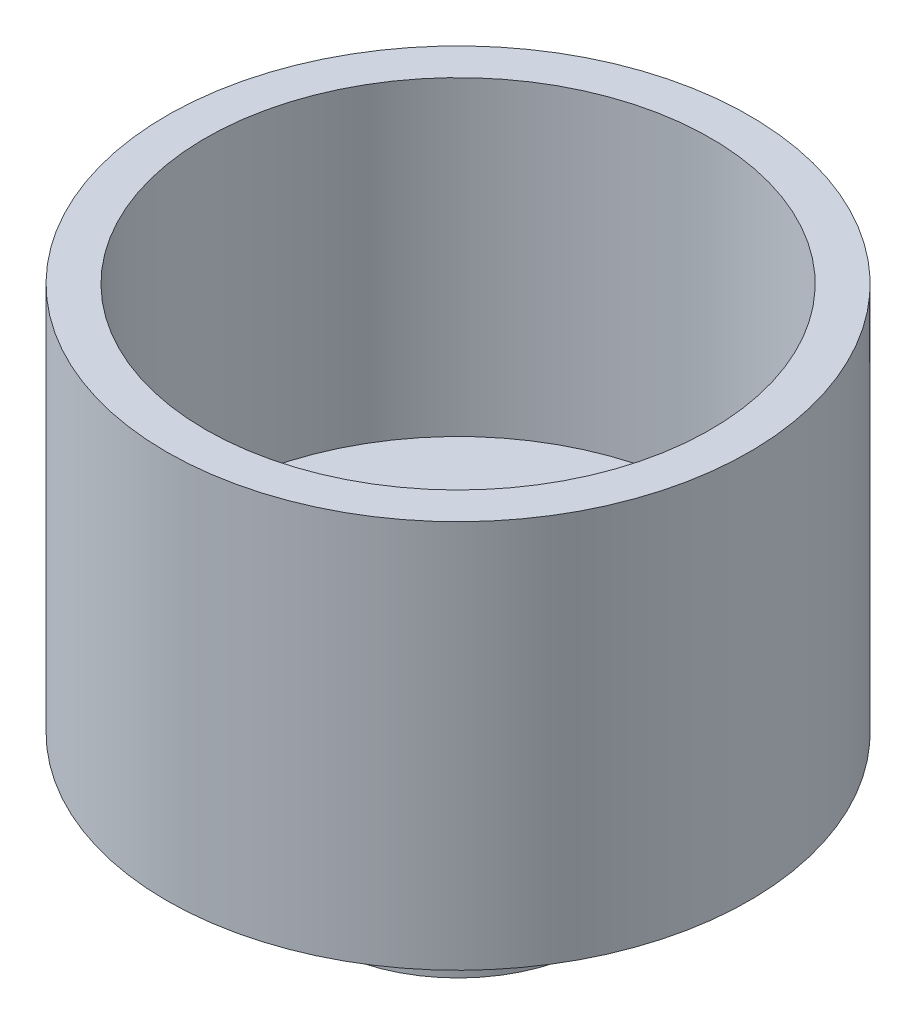
SolidWorks part; units mm, degrees
ref_plane "前视基准面" through (0, 0, 0) normal (0, 0, 1) x (1, 0, 0)
ref_plane "上视基准面" through (0, 0, 0) normal (0, 1, 0) x (1, 0, 0)
ref_plane "右视基准面" through (0, 0, 0) normal (1, 0, 0) x (0, 0, -1)
other "Configuration Table"
sketch "草图1" plane through (0, 0, 0) normal (0, 1, 0) x (1, 0, 0)
  circle A0 centre (0, 0) radius 37.5
  dimension "D1" = 75
extrude "凸台-拉伸1" add sketch "草图1" along normal blind 50 contours A0
sketch "草图2" plane through (0, 50, 0) normal (0, 1, 0) x (1, 0, 0)
  circle A0 centre (0, 0) radius 32.5
  dimension "D1" = 65
extrude "切除-拉伸1" cut sketch "草图2" against normal blind 40
sketch "草图3" plane through (0, 0, 0) normal (0, -1, 0) x (1, 0, 0)
  circle A0 centre (0, 0) radius 17.5
  dimension "D1" = 35
extrude "凸台-拉伸2" add sketch "草图3" along normal blind 15 contours A0
sketch "草图4" plane through (0, -15, 0) normal (0, -1, 0) x (-1, 0, 0)
  circle A0 centre (0, 0) radius 14.5
  dimension "D1" = 29
extrude "切除-拉伸3" cut sketch "草图4" against normal through all contours A0
sketch "草图6" plane through (0, 0, 0) normal (0, -1, 0) x (-1, 0, 0)
  circle A1 centre (-25.9782, 0.985) radius 3.5
  point P4 (0, 0)
  dimension "D2" = 7
extrude "切除-拉伸4" cut sketch "草图6" against normal through all contours A1
sketch "草图8" plane through (0, 0, 0) normal (0, -1, 0) x (1, 0, 0)
  circle A0 centre (-27.3527, 0) radius 3.25
  dimension "D1" = 6.5
extrude "切除-拉伸5" cut sketch "草图8" against normal through all
